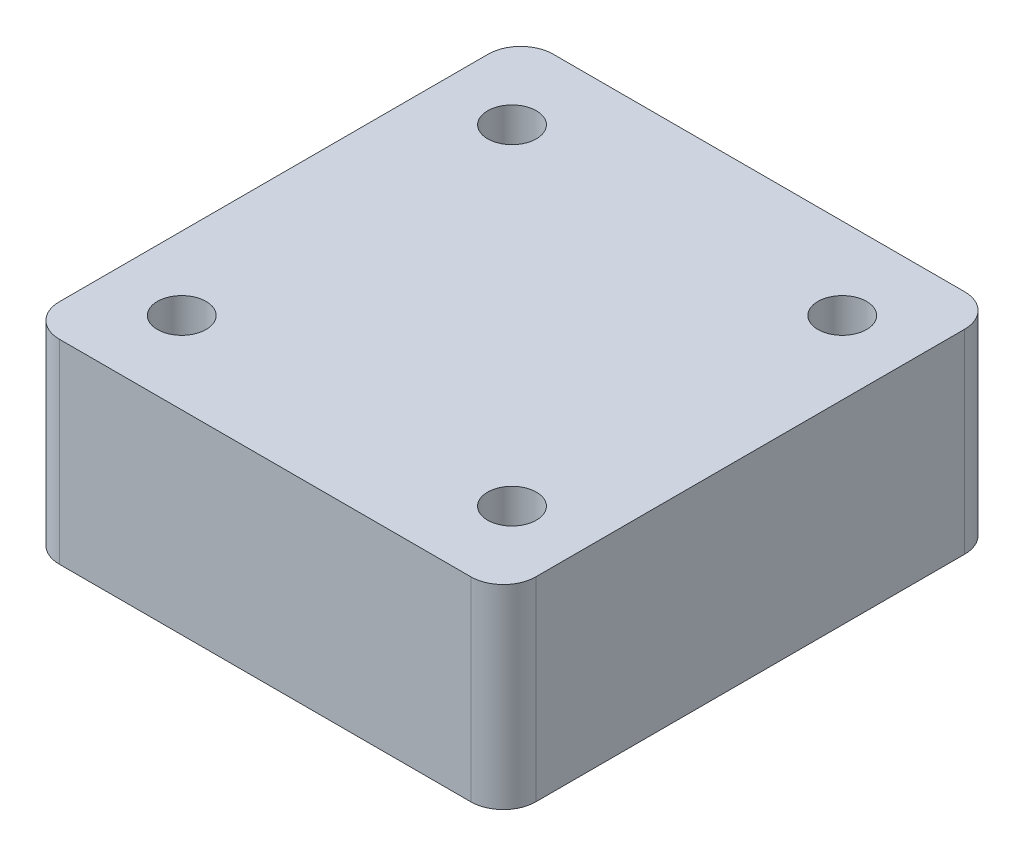
SolidWorks part; units mm, degrees
material "6061 Alloy"
ref_plane "Front Plane" through (0, 0, 0) normal (0, 0, 1) x (1, 0, 0)
ref_plane "Top Plane" through (0, 0, 0) normal (0, 1, 0) x (1, 0, 0)
ref_plane "Right Plane" through (0, 0, 0) normal (1, 0, 0) x (0, 0, -1)
sketch "Sketch1" plane through (0, 0, 0) normal (0, 1, 0) x (1, 0, 0)
  line L1 (-22, 22.8) -> (22, 22.8)
  line L2 (-22, 22.8) -> (-22, -22.8)
  line L3 (-22, -22.8) -> (22, -22.8)
  line L4 (22, 22.8) -> (22, -22.8)
  line L5 (-22, 22.8) -> (22, -22.8) construction
  line L6 (-22, -22.8) -> (22, 22.8) construction
  point P0 (0, 0)
  dimension "D1" = 44
  dimension "D2" = 45.6
extrude "Boss-Extrude1" add sketch "Sketch1" along normal blind 18
fillet "Fillet1" radius 3 4 edges at (-22, 9, -22.8) (22, 9, -22.8) (22, 9, 22.8) (-22, 9, 22.8)
hole_wizard "M4 Clearance Hole1" positions "Sketch2" profile "Sketch3" hole size "M4" standard "ANSI Metric" end condition through all
sketch "Sketch2" plane through (0, 18, 0) normal (0, 1, 0) x (1, 0, 0)
  line L1 (-15.25, 15.25) -> (15.25, 15.25) construction
  line L2 (-15.25, 15.25) -> (-15.25, -15.25) construction
  line L3 (-15.25, -15.25) -> (15.25, -15.25) construction
  line L4 (15.25, 15.25) -> (15.25, -15.25) construction
  line L5 (-15.25, 15.25) -> (15.25, -15.25) construction
  line L6 (-15.25, -15.25) -> (15.25, 15.25) construction
  point P2 (15.25, -15.25)
  point P35 (-15.25, 15.25)
  point P36 (-15.25, -15.25)
  point P37 (15.25, 15.25)
  dimension "D1" = 30.5
sketch "Sketch3" plane through (15.25, 18, 15.25) normal (1, 0, 0) x (0, 0, 1)
  line L0 (0, 0) -> (0, 18)
  line L1 (0, 18) -> (2.25, 18)
  line L2 (2.25, 18) -> (2.25, 0)
  line L5 (2.25, 0) -> (0, 0)
  line L11 (0, -6.35) -> (0, 107.95) construction
  dimension "Thru Hole Dia." = 4.5
  dimension "Thru Hole Depth" = 18
